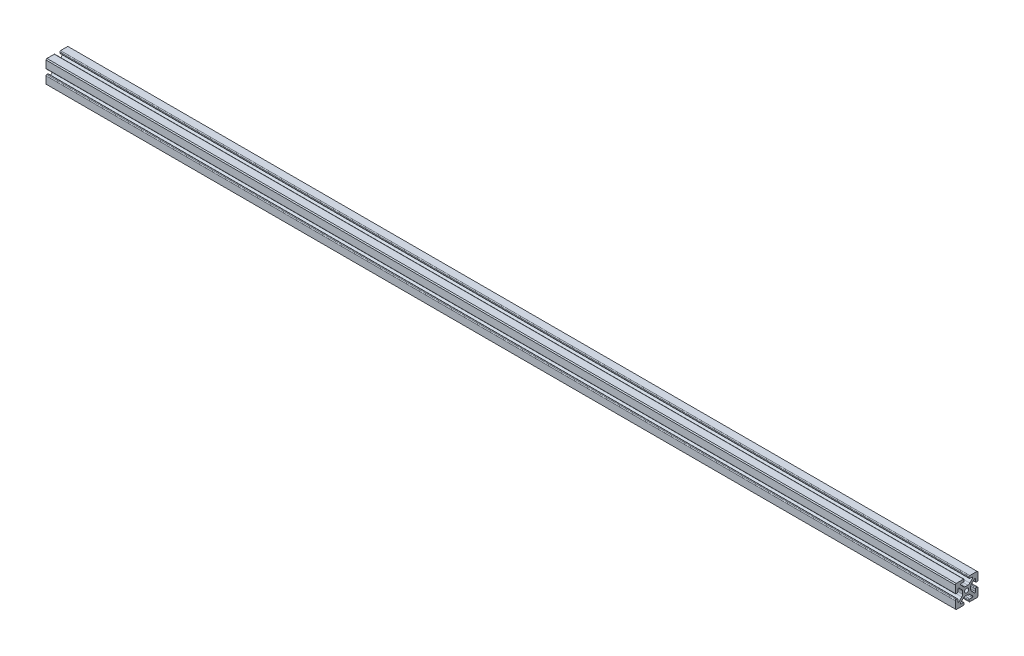
SolidWorks part; units mm, degrees
ref_plane "Front Plane" through (0, 0, 0) normal (0, 0, 1) x (1, 0, 0)
ref_plane "Top Plane" through (0, 0, 0) normal (0, 1, 0) x (1, 0, 0)
ref_plane "Right Plane" through (0, 0, 0) normal (1, 0, 0) x (0, 0, -1)
ref_plane "Plane1" through (0, 0, 0) normal (-1, 0, 0) x (0, -1, 0)
sketch "Sketch1" plane through (0, 0, 0) normal (-1, 0, 0) x (0, -1, 0)
  line L0 (19.05, 5.334) -> (19.05, 17.526)
  line L1 (19.05, 17.526) -> (17.526, 19.05)
  line L2 (17.526, 19.05) -> (5.334, 19.05)
  line L3 (4.064, 17.78) -> (4.064, 16.1266)
  line L4 (5.334, 14.8566) -> (9.0964, 14.8566)
  line L5 (10.287, 13.666) -> (10.287, 13.6538)
  line L6 (9.9383, 12.8119) -> (5.2776, 8.1513)
  line L7 (1.91, 6.7564) -> (-1.91, 6.7564)
  line L8 (-5.2776, 8.1513) -> (-9.9383, 12.8119)
  line L9 (-10.287, 13.6538) -> (-10.287, 13.666)
  line L10 (-9.0964, 14.8566) -> (-5.334, 14.8566)
  line L11 (-4.064, 16.1266) -> (-4.064, 17.78)
  line L12 (-5.334, 19.05) -> (-17.526, 19.05)
  line L13 (-17.526, 19.05) -> (-19.05, 17.526)
  line L14 (-19.05, 17.526) -> (-19.05, 5.334)
  line L15 (-17.78, 4.064) -> (-16.1266, 4.064)
  line L16 (-14.8566, 5.334) -> (-14.8566, 9.0964)
  line L17 (-13.666, 10.287) -> (-13.6538, 10.287)
  line L18 (-12.8119, 9.9383) -> (-8.1513, 5.2776)
  line L19 (-6.7564, 1.91) -> (-6.7564, -1.91)
  line L20 (-8.1513, -5.2776) -> (-12.8119, -9.9383)
  line L21 (-13.6538, -10.287) -> (-13.666, -10.287)
  line L22 (-14.8566, -9.0964) -> (-14.8566, -5.334)
  line L23 (-16.1266, -4.064) -> (-17.78, -4.064)
  line L24 (-19.05, -5.334) -> (-19.05, -17.526)
  line L25 (-19.05, -17.526) -> (-17.526, -19.05)
  line L26 (-17.526, -19.05) -> (-5.334, -19.05)
  line L27 (-4.064, -17.78) -> (-4.064, -16.1266)
  line L28 (-5.334, -14.8566) -> (-9.0964, -14.8566)
  line L29 (-10.287, -13.666) -> (-10.287, -13.6538)
  line L30 (-9.9383, -12.8119) -> (-5.2776, -8.1513)
  line L31 (-1.91, -6.7564) -> (1.91, -6.7564)
  line L32 (5.2776, -8.1513) -> (9.9383, -12.8119)
  line L33 (10.287, -13.6538) -> (10.287, -13.666)
  line L34 (9.0964, -14.8566) -> (5.334, -14.8566)
  line L35 (4.064, -16.1266) -> (4.064, -17.78)
  line L36 (5.334, -19.05) -> (17.526, -19.05)
  line L37 (17.526, -19.05) -> (19.05, -17.526)
  line L38 (19.05, -17.526) -> (19.05, -5.334)
  line L39 (17.78, -4.064) -> (16.1266, -4.064)
  line L40 (14.8566, -5.334) -> (14.8566, -9.0964)
  line L41 (13.666, -10.287) -> (13.6538, -10.287)
  line L42 (12.8119, -9.9383) -> (8.1513, -5.2776)
  line L43 (6.7564, -1.91) -> (6.7564, 1.91)
  line L44 (8.1513, 5.2776) -> (12.8119, 9.9383)
  line L45 (13.6538, 10.287) -> (13.666, 10.287)
  line L46 (14.8566, 9.0964) -> (14.8566, 5.334)
  line L47 (16.1266, 4.064) -> (17.78, 4.064)
  arc A0 (17.78, 4.064) -> (19.05, 5.334) centre (17.78, 5.334) ccw
  arc A1 (5.334, 19.05) -> (4.064, 17.78) centre (5.334, 17.78) ccw
  arc A2 (4.064, 16.1266) -> (5.334, 14.8566) centre (5.334, 16.1266) ccw
  arc A3 (9.0964, 14.8566) -> (10.287, 13.666) centre (9.0964, 13.666) cw
  arc A4 (10.287, 13.6538) -> (9.9383, 12.8119) centre (9.0964, 13.6538) cw
  arc A5 (5.2776, 8.1513) -> (1.91, 6.7564) centre (1.91, 11.5189) cw
  arc A6 (-1.91, 6.7564) -> (-5.2776, 8.1513) centre (-1.91, 11.5189) cw
  arc A7 (-9.9383, 12.8119) -> (-10.287, 13.6538) centre (-9.0964, 13.6538) cw
  arc A8 (-10.287, 13.666) -> (-9.0964, 14.8566) centre (-9.0964, 13.666) cw
  arc A9 (-5.334, 14.8566) -> (-4.064, 16.1266) centre (-5.334, 16.1266) ccw
  arc A10 (-4.064, 17.78) -> (-5.334, 19.05) centre (-5.334, 17.78) ccw
  arc A11 (-19.05, 5.334) -> (-17.78, 4.064) centre (-17.78, 5.334) ccw
  arc A12 (-16.1266, 4.064) -> (-14.8566, 5.334) centre (-16.1266, 5.334) ccw
  arc A13 (-14.8566, 9.0964) -> (-13.666, 10.287) centre (-13.666, 9.0964) cw
  arc A14 (-13.6538, 10.287) -> (-12.8119, 9.9383) centre (-13.6538, 9.0964) cw
  arc A15 (-8.1513, 5.2776) -> (-6.7564, 1.91) centre (-11.5189, 1.91) cw
  arc A16 (-6.7564, -1.91) -> (-8.1513, -5.2776) centre (-11.5189, -1.91) cw
  arc A17 (-12.8119, -9.9383) -> (-13.6538, -10.287) centre (-13.6538, -9.0964) cw
  arc A18 (-13.666, -10.287) -> (-14.8566, -9.0964) centre (-13.666, -9.0964) cw
  arc A19 (-14.8566, -5.334) -> (-16.1266, -4.064) centre (-16.1266, -5.334) ccw
  arc A20 (-17.78, -4.064) -> (-19.05, -5.334) centre (-17.78, -5.334) ccw
  arc A21 (-5.334, -19.05) -> (-4.064, -17.78) centre (-5.334, -17.78) ccw
  arc A22 (-4.064, -16.1266) -> (-5.334, -14.8566) centre (-5.334, -16.1266) ccw
  arc A23 (-9.0964, -14.8566) -> (-10.287, -13.666) centre (-9.0964, -13.666) cw
  arc A24 (-10.287, -13.6538) -> (-9.9383, -12.8119) centre (-9.0964, -13.6538) cw
  arc A25 (-5.2776, -8.1513) -> (-1.91, -6.7564) centre (-1.91, -11.5189) cw
  arc A26 (1.91, -6.7564) -> (5.2776, -8.1513) centre (1.91, -11.5189) cw
  arc A27 (9.9383, -12.8119) -> (10.287, -13.6538) centre (9.0964, -13.6538) cw
  arc A28 (10.287, -13.666) -> (9.0964, -14.8566) centre (9.0964, -13.666) cw
  arc A29 (5.334, -14.8566) -> (4.064, -16.1266) centre (5.334, -16.1266) ccw
  arc A30 (4.064, -17.78) -> (5.334, -19.05) centre (5.334, -17.78) ccw
  arc A31 (19.05, -5.334) -> (17.78, -4.064) centre (17.78, -5.334) ccw
  arc A32 (16.1266, -4.064) -> (14.8566, -5.334) centre (16.1266, -5.334) ccw
  arc A33 (14.8566, -9.0964) -> (13.666, -10.287) centre (13.666, -9.0964) cw
  arc A34 (13.6538, -10.287) -> (12.8119, -9.9383) centre (13.6538, -9.0964) cw
  arc A35 (8.1513, -5.2776) -> (6.7564, -1.91) centre (11.5189, -1.91) cw
  arc A36 (6.7564, 1.91) -> (8.1513, 5.2776) centre (11.5189, 1.91) cw
  arc A37 (12.8119, 9.9383) -> (13.6538, 10.287) centre (13.6538, 9.0964) cw
  arc A38 (13.666, 10.287) -> (14.8566, 9.0964) centre (13.666, 9.0964) cw
  arc A39 (14.8566, 5.334) -> (16.1266, 4.064) centre (16.1266, 5.334) ccw
  circle A40 centre (0, 0) radius 3.4036
extrude "Boss-Extrude1" add sketch "Sketch1" against normal blind 1524
